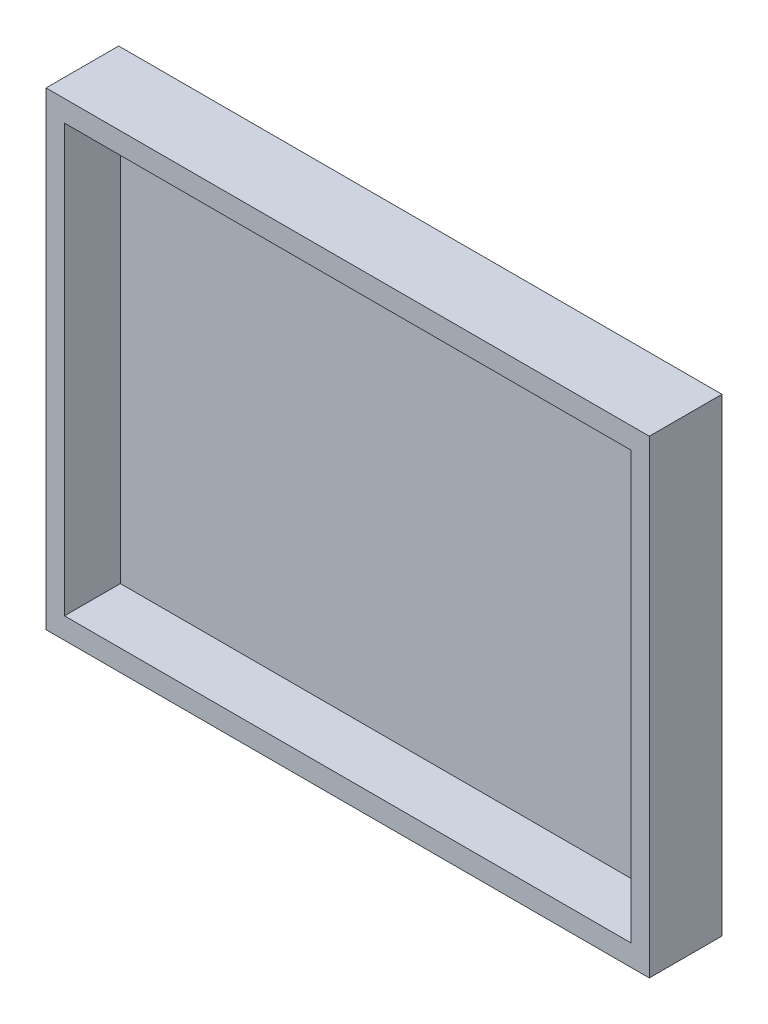
SolidWorks part; units mm, degrees
ref_plane "Plan de face" through (0, 0, 0) normal (0, 0, 1) x (1, 0, 0)
ref_plane "Plan de dessus" through (0, 0, 0) normal (0, 1, 0) x (1, 0, 0)
ref_plane "Plan de droite" through (0, 0, 0) normal (1, 0, 0) x (0, 0, -1)
sketch "Esquisse1" plane through (0, 0, 0) normal (0, 0, 1) x (1, 0, 0)
  circle A0 centre (0, 0) radius 7.5
  circle A1 centre (0, 0) radius 4.5
  dimension "D1" = 15
  dimension "D2" = 3
extrude "Boss.-Extru.1" add sketch "Esquisse1" along normal blind 10
sketch "Esquisse2" plane through (0, 0, 10) normal (0, 0, 1) x (1, 0, 0)
  line L1 (-27, -21) -> (27, -21)
  line L2 (-27, -21) -> (-27, 21)
  line L3 (-27, 21) -> (27, 21)
  line L4 (27, -21) -> (27, 21)
  line L5 (-27, -21) -> (27, 21) construction
  line L6 (-27, 21) -> (27, -21) construction
  point P0 (0, 0)
  dimension "D1" = 42
  dimension "D2" = 54
extrude "Boss.-Extru.2" add sketch "Esquisse2" along normal blind 6.5
sketch "Esquisse4" plane through (0, 0, 16.5) normal (0, 0, 1) x (1, 0, 0)
  line L1 (-25.35, -19.1) -> (25.35, -19.1)
  line L2 (-25.35, -19.1) -> (-25.35, 19.1)
  line L3 (-25.35, 19.1) -> (25.35, 19.1)
  line L4 (25.35, -19.1) -> (25.35, 19.1)
  line L5 (-25.35, -19.1) -> (25.35, 19.1) construction
  line L6 (-25.35, 19.1) -> (25.35, -19.1) construction
  point P0 (0, 0)
  dimension "D1" = 38.2
  dimension "D2" = 50.7
extrude "Enlèv. mat.-Extru.2" cut sketch "Esquisse4" against normal blind 5
